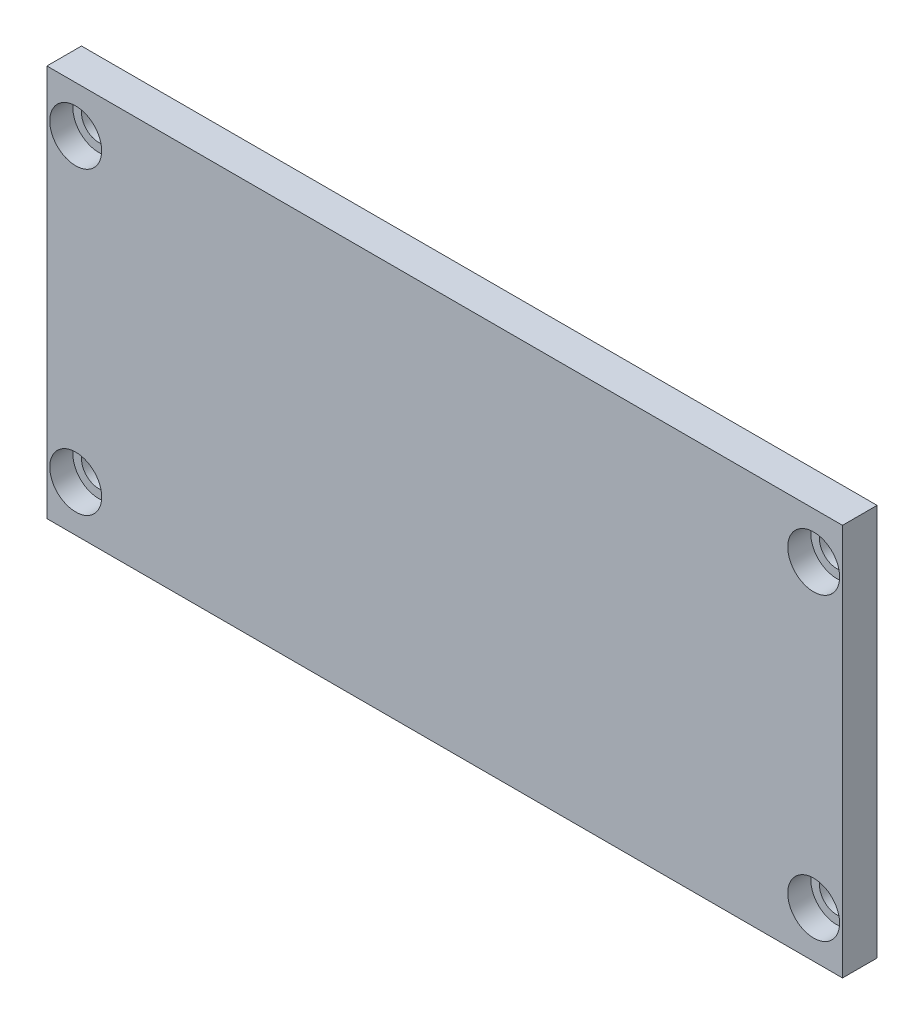
SolidWorks part; units mm, degrees
ref_plane "Płaszczyzna przednia" through (0, 0, 0) normal (0, 0, 1) x (1, 0, 0)
ref_plane "Płaszczyzna górna" through (0, 0, 0) normal (0, 1, 0) x (1, 0, 0)
ref_plane "Płaszczyzna prawa" through (0, 0, 0) normal (1, 0, 0) x (0, 0, -1)
sketch "Szkic1" plane through (0, 0, 0) normal (0, 0, 1) x (1, 0, 0)
  line L0 (0, 34) -> (69, 34)
  line L3 (69, 34) -> (69, 0)
  line L4 (69, 0) -> (0, 0)
  line L5 (0, 0) -> (0, 34)
  point P2 (25.6836, 2088.1845)
  point P8 (26.0064, 2087.9381)
  dimension "D1" = 69
  dimension "D2" = 34
extrude "Dodanie-wyciągnięcie1" add sketch "Szkic1" along normal blind 3
sketch "Szkic2" plane through (0, 0, 3) normal (0, 0, 1) x (1, 0, 0)
  line L0 (0, 17) -> (69, 17) construction
  line L1 (34.5, 34) -> (34.5, 0) construction
  line L2 (2.5, 30) -> (66.5, 4) construction
  line L4 (69, 0) -> (69, 34)
  line L5 (69, 34) -> (0, 34)
  line L6 (0, 34) -> (0, 0)
  line L7 (0, 0) -> (69, 0)
  line L8 (69, 0) -> (69, 34) construction
  line L9 (69, 34) -> (0, 34) construction
  line L10 (0, 34) -> (0, 0) construction
  line L11 (0, 0) -> (69, 0) construction
  line L12 (69, 0) -> (69, 34) construction
  circle A0 centre (2.5, 30) radius 1.5
  circle A1 centre (2.5, 4) radius 1.5
  circle A2 centre (66.5, 4) radius 1.5
  circle A3 centre (66.5, 30) radius 1.5
  point P16 (34.5, 17)
  point P17 (34.5, 17)
  dimension "D4" = 3
  dimension "D1" = 64
  dimension "D2" = 26
  dimension "D3" = 0
extrude "Wytnij-wyciągnięcie1" cut sketch "Szkic2" against normal blind 3
sketch "Szkic3" plane through (0, 0, 3) normal (0, 0, 1) x (1, 0, 0)
  circle A0 centre (2.5, 30) radius 2.25
  circle A1 centre (2.5, 30) radius 1.5 construction
  circle A2 centre (66.5, 30) radius 2.25
  circle A3 centre (2.5, 4) radius 2.25
  circle A4 centre (66.5, 4) radius 2.25
  circle A5 centre (66.5, 30) radius 1.5 construction
  circle A6 centre (66.5, 4) radius 1.5 construction
  circle A7 centre (2.5, 4) radius 1.5 construction
  dimension "D1" = 4.5
extrude "Wytnij-wyciągnięcie2" cut sketch "Szkic3" against normal blind 2
